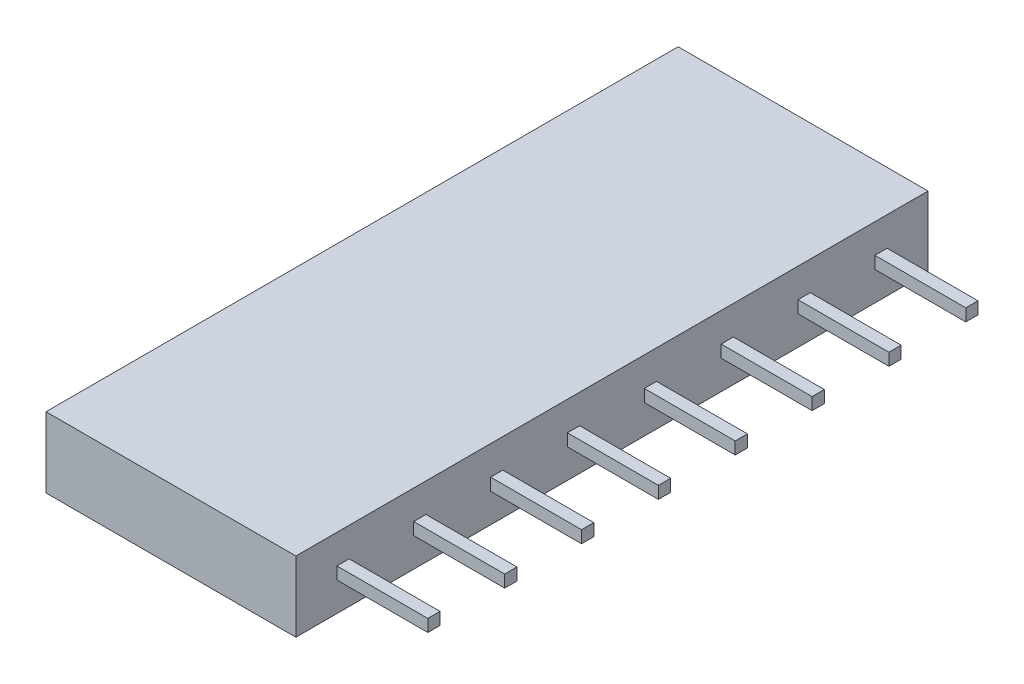
SolidWorks part; units mm, degrees
ref_plane "Front Plane" through (0, 0, 0) normal (0, 0, 1) x (1, 0, 0)
ref_plane "Top Plane" through (0, 0, 0) normal (0, 1, 0) x (1, 0, 0)
ref_plane "Right Plane" through (0, 0, 0) normal (1, 0, 0) x (0, 0, -1)
sketch "Sketch1" plane through (0, 0, 0) normal (0, 1, 0) x (1, 0, 0)
  line L1 (0, 0) -> (8.38, 0)
  line L2 (0, 0) -> (0, 21.2)
  line L3 (0, 21.2) -> (8.38, 21.2)
  line L4 (8.38, 0) -> (8.38, 21.2)
  dimension "D1" = 8.38
  dimension "D2" = 21.2
extrude "Boss-Extrude1" add sketch "Sketch1" along normal blind 2.36
sketch "Sketch2" plane through (8.38, 0, 0) normal (1, 0, 0) x (0, 0, -1)
  line L0 (0, 1.18) -> (1.58, 1.18) construction
  line L3 (0, 2.36) -> (0, 0) construction
  line L4 (1.375, 0.975) -> (1.785, 0.975)
  line L5 (1.375, 0.975) -> (1.375, 1.385)
  line L6 (1.375, 1.385) -> (1.785, 1.385)
  line L7 (1.785, 0.975) -> (1.785, 1.385)
  line L8 (1.375, 0.975) -> (1.785, 1.385) construction
  line L9 (1.375, 1.385) -> (1.785, 0.975) construction
  line L10 (3.9521, 0.975) -> (4.3621, 0.975)
  line L11 (3.9521, 0.975) -> (3.9521, 1.385)
  line L12 (3.9521, 1.385) -> (4.3621, 1.385)
  line L13 (4.3621, 0.975) -> (4.3621, 1.385)
  line L14 (3.9521, 0.975) -> (4.3621, 1.385) construction
  line L15 (3.9521, 1.385) -> (4.3621, 0.975) construction
  line L16 (6.5293, 0.975) -> (6.9393, 0.975)
  line L17 (6.5293, 0.975) -> (6.5293, 1.385)
  line L18 (6.5293, 1.385) -> (6.9393, 1.385)
  line L19 (6.9393, 0.975) -> (6.9393, 1.385)
  line L20 (6.5293, 0.975) -> (6.9393, 1.385) construction
  line L21 (6.5293, 1.385) -> (6.9393, 0.975) construction
  line L22 (9.1064, 0.975) -> (9.5164, 0.975)
  line L23 (9.1064, 0.975) -> (9.1064, 1.385)
  line L24 (9.1064, 1.385) -> (9.5164, 1.385)
  line L25 (9.5164, 0.975) -> (9.5164, 1.385)
  line L26 (9.1064, 0.975) -> (9.5164, 1.385) construction
  line L27 (9.1064, 1.385) -> (9.5164, 0.975) construction
  line L28 (11.6836, 0.975) -> (12.0936, 0.975)
  line L29 (11.6836, 0.975) -> (11.6836, 1.385)
  line L30 (11.6836, 1.385) -> (12.0936, 1.385)
  line L31 (12.0936, 0.975) -> (12.0936, 1.385)
  line L32 (11.6836, 0.975) -> (12.0936, 1.385) construction
  line L33 (11.6836, 1.385) -> (12.0936, 0.975) construction
  line L34 (14.2607, 0.975) -> (14.6707, 0.975)
  line L35 (14.2607, 0.975) -> (14.2607, 1.385)
  line L36 (14.2607, 1.385) -> (14.6707, 1.385)
  line L37 (14.6707, 0.975) -> (14.6707, 1.385)
  line L38 (14.2607, 0.975) -> (14.6707, 1.385) construction
  line L39 (14.2607, 1.385) -> (14.6707, 0.975) construction
  line L40 (16.8379, 0.975) -> (17.2479, 0.975)
  line L41 (16.8379, 0.975) -> (16.8379, 1.385)
  line L42 (16.8379, 1.385) -> (17.2479, 1.385)
  line L43 (17.2479, 0.975) -> (17.2479, 1.385)
  line L44 (16.8379, 0.975) -> (17.2479, 1.385) construction
  line L45 (16.8379, 1.385) -> (17.2479, 0.975) construction
  line L46 (19.415, 0.975) -> (19.825, 0.975)
  line L47 (19.415, 0.975) -> (19.415, 1.385)
  line L48 (19.415, 1.385) -> (19.825, 1.385)
  line L49 (19.825, 0.975) -> (19.825, 1.385)
  line L50 (19.415, 0.975) -> (19.825, 1.385) construction
  line L51 (19.415, 1.385) -> (19.825, 0.975) construction
  line L52 (1.58, 1.18) -> (4.1571, 1.18) construction
  line L53 (4.1571, 1.18) -> (6.7343, 1.18) construction
  line L54 (6.7343, 1.18) -> (9.3114, 1.18) construction
  line L55 (9.3114, 1.18) -> (11.8886, 1.18) construction
  line L56 (11.8886, 1.18) -> (14.4657, 1.18) construction
  line L57 (14.4657, 1.18) -> (17.0429, 1.18) construction
  line L58 (17.0429, 1.18) -> (19.62, 1.18) construction
  line L59 (19.62, 1.18) -> (21.2, 1.18) construction
  line L60 (21.2, 2.36) -> (21.2, 0) construction
  point P4 (8.0158, 0.566)
  point P6 (1.58, 1.18)
  point P11 (4.1571, 1.18)
  point P16 (6.7343, 1.18)
  point P21 (9.3114, 1.18)
  point P26 (11.8886, 1.18)
  point P31 (14.4657, 1.18)
  point P36 (17.0429, 1.18)
  point P41 (19.62, 1.18)
  point P55 (4.4447, 0.4832)
  point P56 (3.9553, 0.5557)
  point P57 (6.3118, 0.592)
  point P58 (8.6321, 0.6101)
  point P59 (17.1157, 0.6645)
  point P60 (14.7591, 0.6283)
  point P61 (12.3482, 0.6283)
  point P62 (10.0098, 0.6283)
  point P63 (1.5807, 0.975)
  dimension "D1" = 0.41
  dimension "D2" = 18.45
extrude "Boss-Extrude2" add sketch "Sketch2" along normal blind 3.05
sketch "Sketch3" plane through (0, 0, 0) normal (-1, 0, 0) x (0, 0, 1)
  line L0 (-21.2, 1.18) -> (-19.475, 1.18) construction
  line L3 (-21.2, 2.36) -> (-21.2, 0) construction
  line L4 (-19.8, 0.855) -> (-19.15, 0.855)
  line L5 (-19.8, 0.855) -> (-19.8, 1.505)
  line L6 (-19.8, 1.505) -> (-19.15, 1.505)
  line L7 (-19.15, 0.855) -> (-19.15, 1.505)
  line L8 (-19.8, 0.855) -> (-19.15, 1.505) construction
  line L9 (-19.8, 1.505) -> (-19.15, 0.855) construction
  line L10 (-17.2643, 0.855) -> (-16.6143, 0.855)
  line L11 (-17.2643, 0.855) -> (-17.2643, 1.505)
  line L12 (-17.2643, 1.505) -> (-16.6143, 1.505)
  line L13 (-16.6143, 0.855) -> (-16.6143, 1.505)
  line L14 (-17.2643, 0.855) -> (-16.6143, 1.505) construction
  line L15 (-17.2643, 1.505) -> (-16.6143, 0.855) construction
  line L16 (-14.7286, 0.855) -> (-14.0786, 0.855)
  line L17 (-14.7286, 0.855) -> (-14.7286, 1.505)
  line L18 (-14.7286, 1.505) -> (-14.0786, 1.505)
  line L19 (-14.0786, 0.855) -> (-14.0786, 1.505)
  line L20 (-14.7286, 0.855) -> (-14.0786, 1.505) construction
  line L21 (-14.7286, 1.505) -> (-14.0786, 0.855) construction
  line L22 (-12.1929, 0.855) -> (-11.5429, 0.855)
  line L23 (-12.1929, 0.855) -> (-12.1929, 1.505)
  line L24 (-12.1929, 1.505) -> (-11.5429, 1.505)
  line L25 (-11.5429, 0.855) -> (-11.5429, 1.505)
  line L26 (-12.1929, 0.855) -> (-11.5429, 1.505) construction
  line L27 (-12.1929, 1.505) -> (-11.5429, 0.855) construction
  line L28 (-9.6571, 0.855) -> (-9.0071, 0.855)
  line L29 (-9.6571, 0.855) -> (-9.6571, 1.505)
  line L30 (-9.6571, 1.505) -> (-9.0071, 1.505)
  line L31 (-9.0071, 0.855) -> (-9.0071, 1.505)
  line L32 (-9.6571, 0.855) -> (-9.0071, 1.505) construction
  line L33 (-9.6571, 1.505) -> (-9.0071, 0.855) construction
  line L34 (-7.1214, 0.855) -> (-6.4714, 0.855)
  line L35 (-7.1214, 0.855) -> (-7.1214, 1.505)
  line L36 (-7.1214, 1.505) -> (-6.4714, 1.505)
  line L37 (-6.4714, 0.855) -> (-6.4714, 1.505)
  line L38 (-7.1214, 0.855) -> (-6.4714, 1.505) construction
  line L39 (-7.1214, 1.505) -> (-6.4714, 0.855) construction
  line L40 (-4.5857, 0.855) -> (-3.9357, 0.855)
  line L41 (-4.5857, 0.855) -> (-4.5857, 1.505)
  line L42 (-4.5857, 1.505) -> (-3.9357, 1.505)
  line L43 (-3.9357, 0.855) -> (-3.9357, 1.505)
  line L44 (-4.5857, 0.855) -> (-3.9357, 1.505) construction
  line L45 (-4.5857, 1.505) -> (-3.9357, 0.855) construction
  line L46 (-2.05, 0.855) -> (-1.4, 0.855)
  line L47 (-2.05, 0.855) -> (-2.05, 1.505)
  line L48 (-2.05, 1.505) -> (-1.4, 1.505)
  line L49 (-1.4, 0.855) -> (-1.4, 1.505)
  line L50 (-2.05, 0.855) -> (-1.4, 1.505) construction
  line L51 (-2.05, 1.505) -> (-1.4, 0.855) construction
  line L52 (-19.475, 1.18) -> (-16.9393, 1.18) construction
  line L53 (-16.9393, 1.18) -> (-14.4036, 1.18) construction
  line L54 (-14.4036, 1.18) -> (-11.8679, 1.18) construction
  line L55 (-11.8679, 1.18) -> (-9.3321, 1.18) construction
  line L56 (-9.3321, 1.18) -> (-6.7964, 1.18) construction
  line L57 (-6.7964, 1.18) -> (-4.2607, 1.18) construction
  line L58 (-4.2607, 1.18) -> (-1.725, 1.18) construction
  line L59 (-1.725, 1.18) -> (0, 1.18) construction
  line L60 (0, 2.36) -> (0, 0) construction
  point P4 (-11.8006, 1.18)
  point P6 (-19.475, 1.18)
  point P11 (-16.9393, 1.18)
  point P16 (-14.4036, 1.18)
  point P21 (-11.8679, 1.18)
  point P26 (-9.3321, 1.18)
  point P31 (-6.7964, 1.18)
  point P36 (-4.2607, 1.18)
  point P41 (-1.725, 1.18)
  dimension "D1" = 0.65
  dimension "D2" = 18.4
extrude "Cut-Extrude1" cut sketch "Sketch3" against normal blind 3.05
